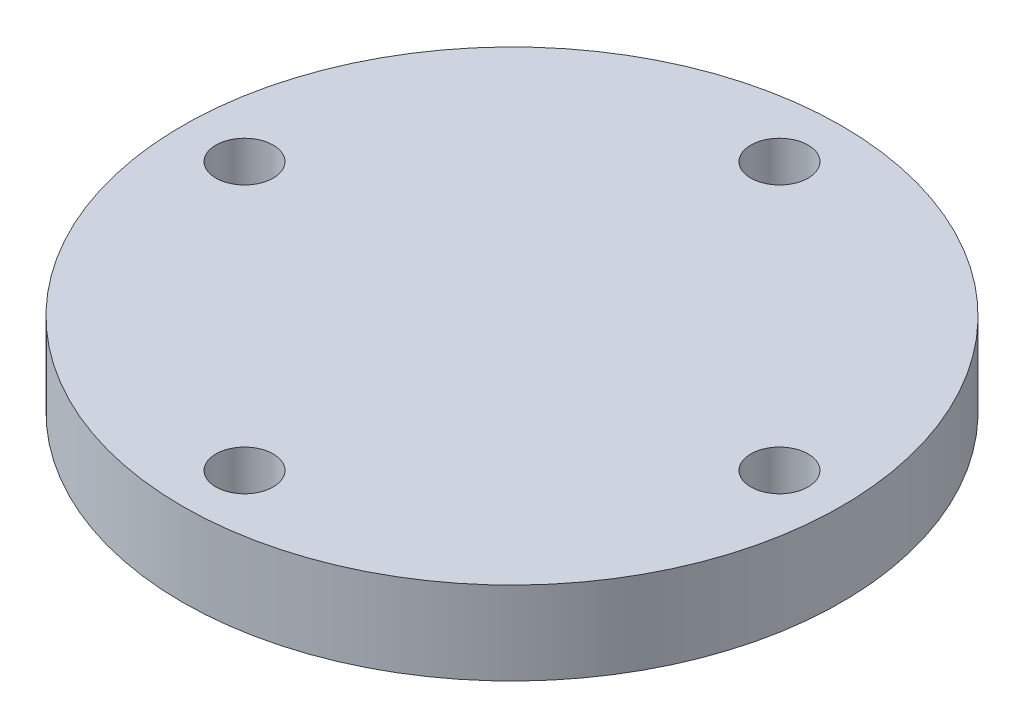
SolidWorks part; units mm, degrees
ref_plane "Спереди" through (0, 0, 0) normal (0, 0, 1) x (1, 0, 0)
ref_plane "Сверху" through (0, 0, 0) normal (0, 1, 0) x (1, 0, 0)
ref_plane "Справа" through (0, 0, 0) normal (1, 0, 0) x (0, 0, -1)
sketch "Эскиз1" plane through (0, 0, 0) normal (0, 1, 0) x (1, 0, 0)
  circle A0 centre (0, 0) radius 34.5
extrude "Вытянуть1" add sketch "Эскиз1" along normal blind 8.7
sketch "Эскиз2" plane through (0, 8.7, 0) normal (0, 1, 0) x (1, 0, 0)
  circle A0 centre (0, 28) radius 3
  circle A1 centre (28, 0) radius 3
  circle A2 centre (0, -28) radius 3
  circle A3 centre (-28, 0) radius 3
  dimension "D1" = 28
extrude "Вытянуть2" cut sketch "Эскиз2" against normal blind 8.7
